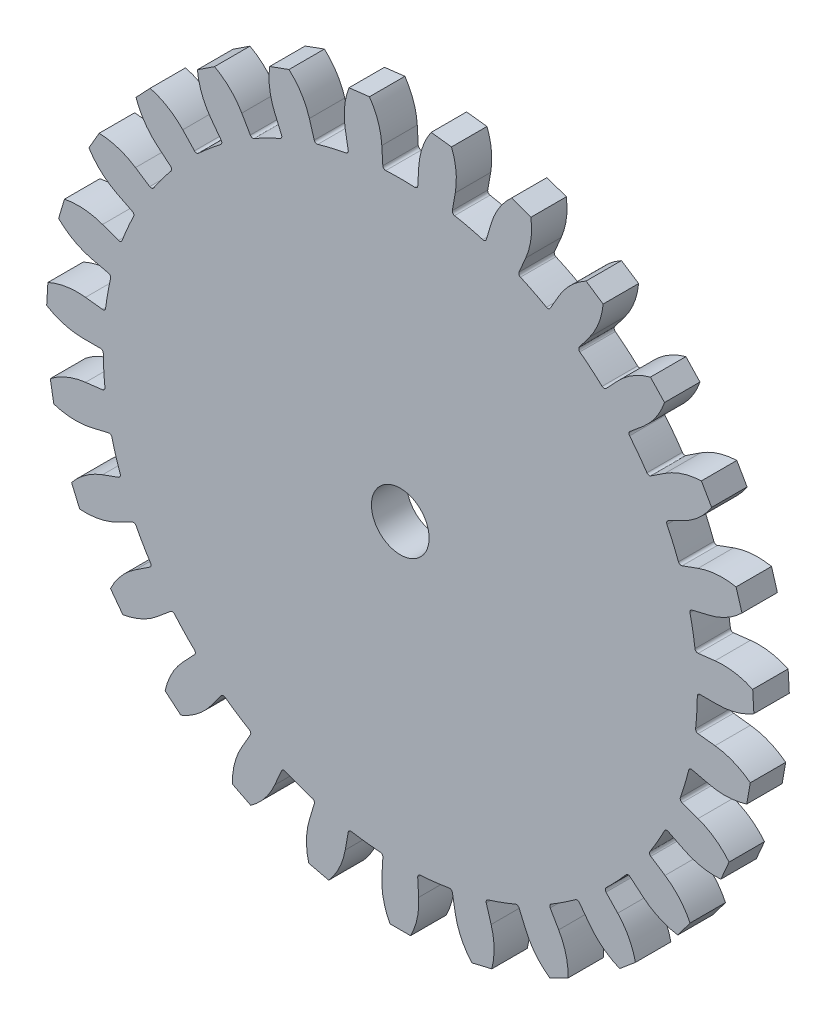
SolidWorks part; units mm, degrees
ref_plane "Front Plane" through (0, 0, 0) normal (0, 0, 1) x (1, 0, 0)
ref_plane "Top Plane" through (0, 0, 0) normal (0, 1, 0) x (1, 0, 0)
ref_plane "Right Plane" through (0, 0, 0) normal (1, 0, 0) x (0, 0, -1)
sketch "Sketch1" plane through (0, 0, 0) normal (0, 0, 1) x (1, 0, 0)
  line L0 (0, 0) -> (0, 38.1593) construction
  line L1 (0, 0) -> (2.4347, 41.7135) construction
  line L2 (0, 0) -> (3.5224, 40.2439) construction
  line L3 (0, 0) -> (4.9479, 42.3322) construction
  line L4 (1.6541, 28.3394) -> (1.5505, 26.5644)
  line L5 (2.7631, 31.569) -> (4.5917, 31.3552)
  line L6 (0, 26.6096) -> (0, 0)
  line L7 (2.7631, 31.569) -> (1.8488, 31.6758) construction
  line L8 (4.926, 27.957) -> (4.6175, 26.206)
  line L9 (6.1366, 25.8924) -> (0, 0)
  line L10 (3.6774, 31.4621) -> (2.7631, 31.569) construction
  circle A0 centre (0, 0) radius 31.6896 construction
  circle A1 centre (0, 0) radius 28.3876 construction
  circle A2 centre (0, 0) radius 26.6096 construction
  arc A3 (0, 26.6096) -> (1.5505, 26.5644) centre (0, 0) cw
  arc A4 (1.6541, 28.3394) -> (2.7631, 31.569) centre (7.9873, 27.9698) cw
  arc A5 (4.926, 27.957) -> (4.5917, 31.3552) centre (-1.3217, 29.0578) ccw
  arc A6 (6.1366, 25.8924) -> (4.6175, 26.206) centre (0, 0) ccw
  point P17 (3.6774, 31.4621)
  dimension "D1" = 6.667
  dimension "D2" = 5.08
  dimension "D3" = 1.778
  dimension "D4" = 1.5505
  dimension "D6" = 63.3793
  dimension "D5" = 0.9205
extrude "Boss-Extrude1" add sketch "Sketch1" along normal blind 3.175 contours L6 L9 A6 L8 A5 L5 A4 L4 A3
fillet "Fillet1" radius 0.254 2 edges at (1.5505, 26.5644, 1.5875) (4.6175, 26.206, 1.5875)
pattern_circular "CirPattern1" count 27 over 360 about axis through (0, 0, 0) along (0, 0, 1) of "Boss-Extrude1", "Fillet1"
sketch "Sketch2" plane through (0, 0, 3.175) normal (0, 0, 1) x (1, 0, 0)
  circle A0 centre (0, 0) radius 2.5828
extrude "Cut-Extrude1" cut sketch "Sketch2" against normal blind 3.175
